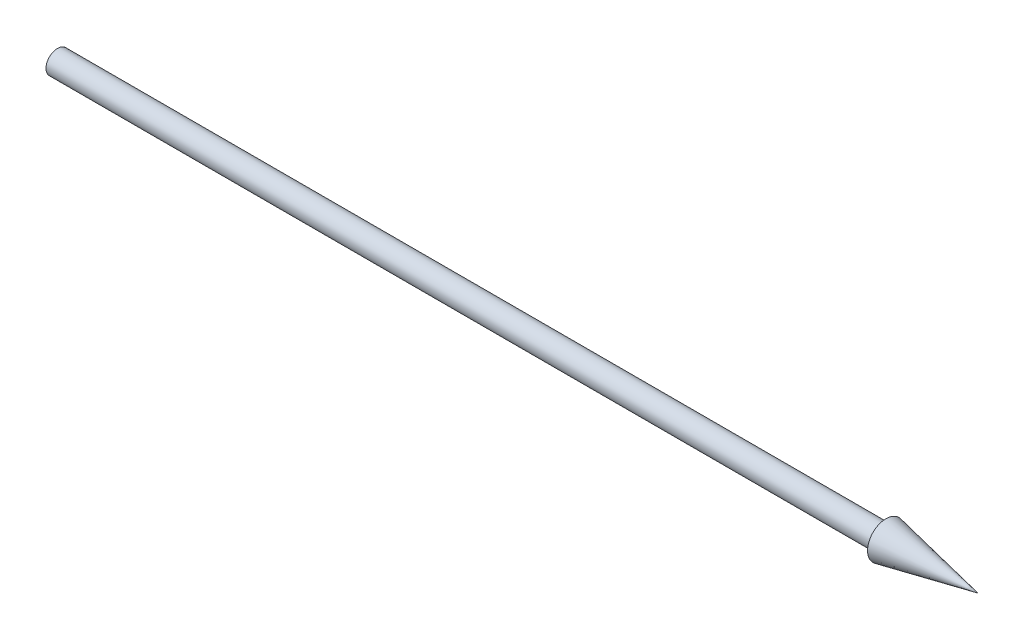
SolidWorks part; units mm, degrees
ref_plane "Plano frontal" through (0, 0, 0) normal (0, 0, 1) x (1, 0, 0)
ref_plane "Plano superior" through (0, 0, 0) normal (0, 1, 0) x (1, 0, 0)
ref_plane "Plano direito" through (0, 0, 0) normal (1, 0, 0) x (0, 0, -1)
sketch "Sketch1" plane through (0, 0, 0) normal (0, 0, 1) x (1, 0, 0)
  line L0 (0, 0) -> (200, 0)
  line L1 (0, 0) -> (0, 2.5)
  line L2 (0, 2.5) -> (180, 2.5)
  line L3 (200, 0) -> (180, 4)
  line L4 (180, 4) -> (180, 2.5)
  dimension "D1" = 200
  dimension "D2" = 2.5
  dimension "D3" = 20
  dimension "D4" = 1.5
revolve "Revolve1" add sketch "Sketch1" angle 360 about L0
